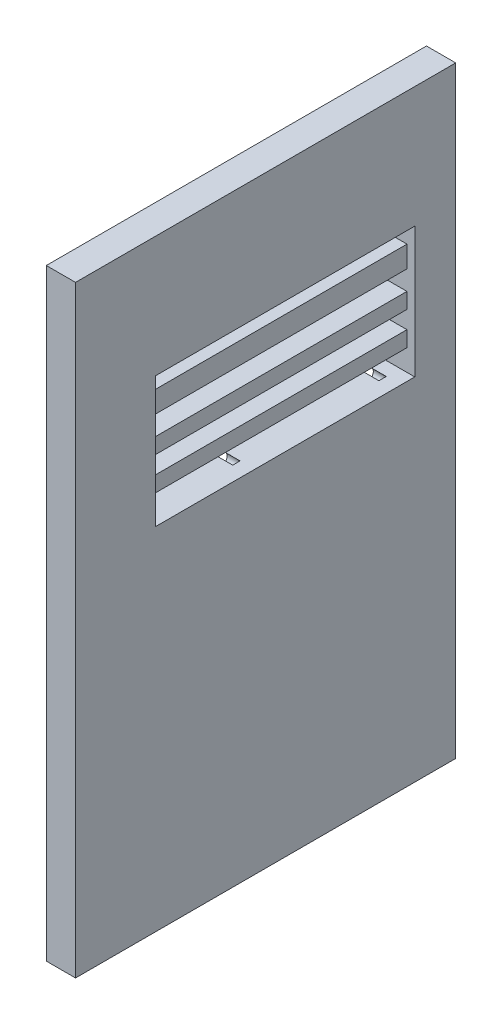
SolidWorks part; units mm, degrees
ref_plane "Alzado" through (0, 0, 0) normal (1, 0, 0) x (0, 1, 0)
ref_plane "Planta" through (0, 0, 0) normal (0, 0, 1) x (0, 1, 0)
ref_plane "Vista lateral" through (0, 0, 0) normal (0, 1, 0) x (-1, 0, 0)
sketch "Croquis1" plane through (0, 0, 0) normal (1, 0, 0) x (0, 1, 0)
  line L0 (69.4077, 154) -> (328.5923, 154) construction
  line L1 (0, 0) -> (309, 0)
  line L2 (0, 0) -> (0, 195)
  line L3 (0, 195) -> (309, 195)
  line L4 (309, 0) -> (309, 195)
  line L5 (69.4077, 21) -> (376.0063, 21) construction
  line L7 (180, 154) -> (191, 154)
  line L8 (180, 154) -> (180, 21)
  line L9 (180, 21) -> (191, 21)
  line L10 (191, 154) -> (191, 21)
  line L11 (199, 154) -> (208, 154)
  line L12 (199, 154) -> (199, 21)
  line L13 (199, 21) -> (208, 21)
  line L14 (208, 154) -> (208, 21)
  line L15 (216, 154) -> (226, 154)
  line L16 (216, 154) -> (216, 21)
  line L17 (216, 21) -> (226, 21)
  line L18 (226, 154) -> (226, 21)
  line L19 (237, 154) -> (247, 154)
  line L20 (237, 154) -> (237, 21)
  line L21 (237, 21) -> (247, 21)
  line L22 (247, 154) -> (247, 21)
  dimension "D1" = 309
  dimension "D2" = 195
  dimension "D3" = 41
  dimension "D4" = 42
  dimension "D5" = 11
  dimension "D6" = 9
  dimension "D7" = 10
  dimension "D8" = 10
  dimension "D9" = 8
  dimension "D10" = 8
  dimension "D11" = 11
  dimension "D12" = 62
extrude "Saliente-Extruir1" add sketch "Croquis1" along normal blind 15
sketch "Croquis2" plane through (15, 0, 0) normal (1, 0, 0) x (0, 1, 0)
  line L1 (180, 154) -> (247, 154)
  line L2 (180, 154) -> (180, 21)
  line L3 (180, 21) -> (247, 21)
  line L4 (0, 195) -> (0, 0)
  line L5 (0, 0) -> (309, 0)
  line L6 (309, 0) -> (309, 195)
  line L7 (309, 195) -> (0, 195)
  line L8 (0, 195) -> (0, 0)
  line L9 (0, 0) -> (309, 0)
  line L10 (309, 0) -> (309, 195)
  line L11 (309, 195) -> (0, 195)
  line L12 (247, 154) -> (247, 21)
  dimension "D1" = 0
extrude "Cortar-Extruir2" cut sketch "Croquis2" against normal blind 4 contours L2 L3 L12 L1
sketch "Croquis3" plane through (0, 0, 0) normal (-1, 0, 0) x (0, -1, 0)
  line L0 (-349.3217, 15) -> (42.6098, 15) construction
  line L1 (-349.3217, 115) -> (22.3431, 115) construction
  line L2 (-349.3217, 105) -> (17.4399, 105) construction
  line L3 (-349.3217, 30) -> (22.3431, 30) construction
  line L4 (0, 0) -> (0, 195)
  line L5 (0, 195) -> (-309, 195)
  line L6 (-309, 195) -> (-309, 0)
  line L7 (-309, 0) -> (0, 0)
  line L8 (0, 0) -> (0, 195)
  line L9 (0, 195) -> (-309, 195)
  line L10 (-309, 195) -> (-309, 0)
  line L11 (-309, 0) -> (0, 0)
  line L12 (-178, 136.9459) -> (-178, 6.4448) construction
  line L13 (-116, 136.9459) -> (-116, 6.4448) construction
  line L14 (-64, 160.7706) -> (-64, 6.4448) construction
  circle A0 centre (-178, 105) radius 2.75
  circle A1 centre (-116, 105) radius 2.75
  circle A2 centre (-178, 30) radius 2.75
  circle A3 centre (-116, 30) radius 2.75
  circle A4 centre (-64, 105) radius 2.75
  circle A5 centre (-64, 30) radius 2.75
  point P30 (-51.2054, 105)
  dimension "D6" = 5.5
  dimension "D2" = 15
  dimension "D3" = 100
  dimension "D4" = 15
  dimension "D5" = 10
  dimension "D7" = 193
  dimension "D8" = 131
  dimension "D9" = 245
  dimension "D1" = 0
extrude "Cortar-Extruir3" cut sketch "Croquis3" against normal blind 7.5 and the other way through all contours A1 | A4 | A5 | A0 | A2 | A3
